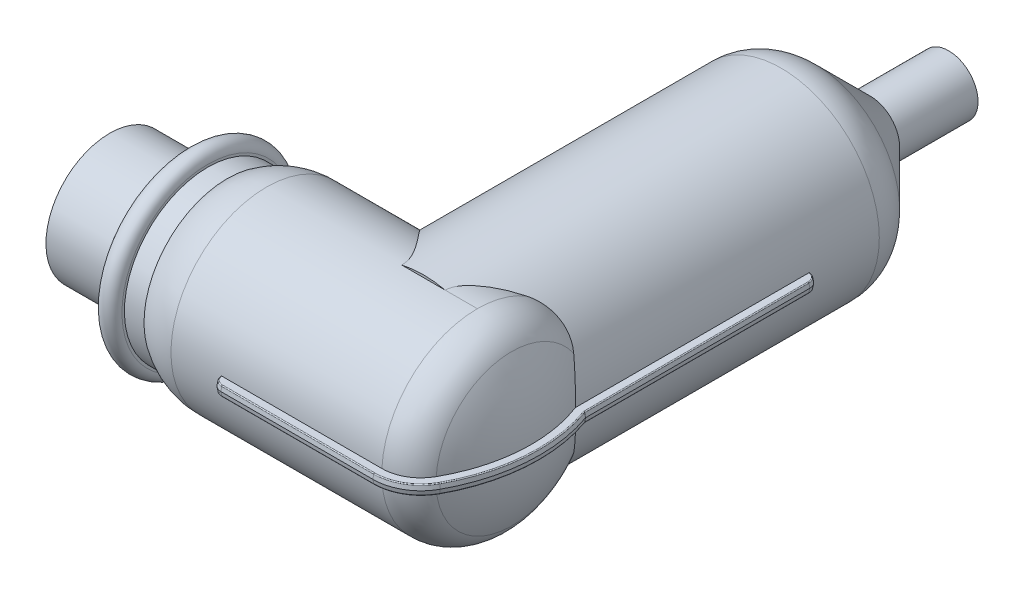
SolidWorks part; units mm, degrees
ref_plane "Front Plane" through (0, 0, 0) normal (0, 0, 1) x (1, 0, 0)
ref_plane "Top Plane" through (0, 0, 0) normal (0, 1, 0) x (1, 0, 0)
ref_plane "Right Plane" through (0, 0, 0) normal (1, 0, 0) x (0, 0, -1)
sketch "Sketch1" plane through (0, 0, 0) normal (0, 0, 1) x (1, 0, 0)
  line L0 (8, 6.5) -> (8, 8.75)
  line L2 (10, 8.75) -> (10, 8.5)
  line L3 (10, 8.5) -> (12, 8.5)
  line L4 (0, 0) -> (43, 0)
  line L5 (37.5, 9.75) -> (16, 9.75)
  line L6 (0, 0) -> (-5.7927, 0) construction
  line L7 (43, 0) -> (43, 7.3633) construction
  line L8 (8, 6.5) -> (0, 6.5)
  line L9 (0, 6.5) -> (0, 0)
  arc A0 (8, 8.75) -> (10, 8.75) centre (9, 8.75) cw
  arc A1 (16, 9.75) -> (12, 8.5) centre (16, 2.725) ccw
  arc A2 (43, 0) -> (40.9903, 7.704) centre (27.2292, 0) ccw
  arc A3 (37.5, 9.75) -> (40.9903, 7.704) centre (37.5, 5.75) cw
  dimension "D9" = 4
  dimension "D1" = 2
  dimension "D2" = 17.5
  dimension "D3" = 4
  dimension "D4" = 8
  dimension "D5" = 17
  dimension "D6" = 35
  dimension "D7" = 29.5
  dimension "D8" = 19.5
  dimension "D10" = 13
  dimension "D11" = 8
revolve "Revolve1" add sketch "Sketch1" angle 360 about L6
sketch "Sketch2" plane through (0, 0, 0) normal (0, 1, 0) x (1, 0, 0)
  line L0 (32, 0) -> (32, -17.9723) construction
  line L1 (32, 0) -> (0, 0) construction
  line L2 (42, 0) -> (32, 0)
  line L3 (32, 0) -> (32, 53.5711)
  line L4 (32, 53.5711) -> (35, 53.5711)
  line L5 (35, 53.5711) -> (35, 45.5711)
  line L6 (35, 45.5711) -> (40.5355, 40.0355)
  line L7 (42, 36.5) -> (42, 0)
  arc A0 (40.5355, 40.0355) -> (42, 36.5) centre (37, 36.5) cw
  dimension "D6" = 6
  dimension "D5" = 5
  dimension "D1" = 32
  dimension "D2" = 45
  dimension "D3" = 36.5
  dimension "D4" = 20
  dimension "D8" = 8
revolve "Revolve2" add sketch "Sketch2" angle 360 about L0
sketch "Sketch3" plane through (0, 0, 0) normal (0, 1, 0) x (1, 0, 0)
  line L0 (37.5, 5.0312) -> (37.5, -9.75) construction
  line L1 (41.9, 5.4612) -> (41.9, 29.5)
  line L2 (0, 0) -> (43, 0) construction
  line L3 (21, -9.65) -> (37.5, -9.65)
  line L4 (32, 0) -> (32, 53.5711) construction
  line L5 (22.1, 9.65) -> (18, 9.65)
  line L7 (22.1, 29.5) -> (22.1, 9.65)
  line L8 (22, 36.5) -> (42, 36.5) construction
  line L9 (16, -9.75) -> (16, 9.75) construction
  line L10 (22, -10.65) -> (37.5, -10.65)
  line L11 (42.9, 5.6356) -> (42.9, 28.5)
  line L12 (21.1, 28.5) -> (21.1, 10.65)
  line L13 (21.1, 10.65) -> (19, 10.65)
  line L14 (42.9, 5.6356) -> (42.9, 29.5) construction
  line L15 (21.1, 29.5) -> (21.1, 10.65) construction
  line L16 (21.1, 10.65) -> (18, 10.65) construction
  line L17 (21, -10.65) -> (37.5, -10.65) construction
  line L18 (32, 0) -> (0, 0) construction
  arc A0 (40.9231, -7.6187) -> (41.9, 5.4612) centre (26.9673, 0) ccw construction
  arc A1 (40.9231, -7.6187) -> (41.9, 5.4612) centre (26.9673, 0) ccw
  arc A3 (37.5, -9.65) -> (40.9231, -7.6187) centre (37.5, -5.75) ccw
  arc A4 (37.5, -10.65) -> (41.8008, -8.0979) centre (37.5, -5.75) ccw
  arc A5 (41.8008, -8.0979) -> (42.9, 5.6356) centre (26.9673, 0) ccw
  arc A6 (42.9, 28.5) -> (41.9, 29.5) centre (41.9, 28.5) ccw
  arc A7 (21.1, 28.5) -> (22.1, 29.5) centre (22.1, 28.5) cw
  arc A8 (19, 10.65) -> (18, 9.65) centre (19, 9.65) ccw
  arc A9 (22, -10.65) -> (21, -9.65) centre (22, -9.65) cw
  dimension "D11" = 3.9
  dimension "D12" = 15.9
  dimension "D1" = 7
  dimension "D2" = 7
  dimension "D3" = 2
  dimension "D4" = 5
  dimension "D7" = 9.9
  dimension "D8" = 9.65
  dimension "D9" = 9.9
  dimension "D10" = 9.65
  dimension "D5" = 1
  dimension "D6" = 1
extrude "Boss-Extrude1" add sketch "Sketch3" along normal mid plane 1 draft 10
fillet "Fillet1" radius 0.1 24 edges at (21.4248, 0.5, -29.1128) (21.4248, -0.5, -29.1128) (21.1882, 0.5, -19.5309) (21.1882, -0.5, -19.5309) (18.3872, -0.5, -10.3252) (20.0941, 0.5, -10.5618) (42.5752, 0.5, -29.1128) (21.3872, 0.5, 10.3252) (29.75, 0.5, 10.5618) (39.9555, 0.5, 9.8881) (42.5752, -0.5, -29.1128) (43.7262, -0.5, 1.3337) (39.9555, -0.5, 9.8881) (29.75, -0.5, 10.5618) (20.0941, -0.5, -10.5618) (21.1441, -0.25, -10.6059) (21.1441, 0.25, -10.6059) (18.3872, 0.5, -10.3252) (42.8118, 0.5, -17.0602) (43.7262, 0.5, 1.3337) (42.8118, -0.5, -17.0602) (21.3872, -0.5, 10.3252)
